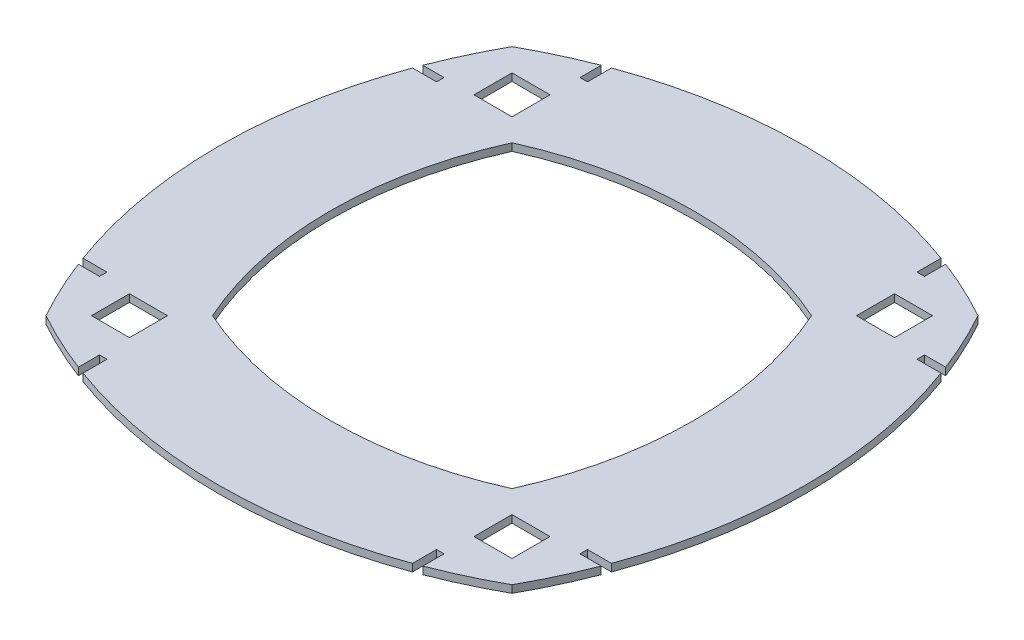
SolidWorks part; units mm, degrees
ref_plane "Front Plane" through (0, 0, 0) normal (0, 0, 1) x (1, 0, 0)
ref_plane "Top Plane" through (0, 0, 0) normal (0, 1, 0) x (1, 0, 0)
ref_plane "Right Plane" through (0, 0, 0) normal (1, 0, 0) x (0, 0, -1)
sketch "Sketch1" plane through (0, 0, 0) normal (0, 1, 0) x (1, 0, 0)
  line L0 (115, 140.4) -> (115, 115)
  line L1 (-155.565, 155.565) -> (155.565, 155.565) construction
  line L2 (-155.565, 155.565) -> (-155.565, -155.565) construction
  line L3 (-155.565, -155.565) -> (155.565, -155.565) construction
  line L4 (155.565, 155.565) -> (155.565, -155.565) construction
  line L5 (0, -155.565) -> (0, 155.565) construction
  line L6 (-155.565, 0) -> (155.565, 0) construction
  line L7 (-140.4, 140.4) -> (140.4, 140.4) construction
  line L8 (-140.4, 140.4) -> (-140.4, -140.4) construction
  line L9 (-140.4, -140.4) -> (140.4, -140.4) construction
  line L10 (140.4, 140.4) -> (140.4, -140.4) construction
  line L11 (0, -140.4) -> (0, 140.4) construction
  line L12 (-140.4, 0) -> (140.4, 0) construction
  line L13 (-140.4, 140.4) -> (-115, 140.4)
  line L14 (-140.4, 140.4) -> (-140.4, 115)
  line L15 (-140.4, 115) -> (-115, 115)
  line L16 (-115, 140.4) -> (-115, 115)
  line L17 (140.4, 140.4) -> (115, 140.4)
  line L18 (140.4, 140.4) -> (140.4, 115)
  line L19 (140.4, 115) -> (115, 115)
  line L20 (140.4, -140.4) -> (140.4, -115)
  line L21 (140.4, -140.4) -> (115, -140.4)
  line L22 (115, -140.4) -> (115, -115)
  line L23 (140.4, -115) -> (115, -115)
  line L24 (-115, -140.4) -> (-115, -115)
  line L25 (-140.4, -140.4) -> (-115, -140.4)
  line L26 (-140.4, -140.4) -> (-140.4, -115)
  line L27 (-140.4, -115) -> (-115, -115)
  line L28 (115, 160.4) -> (110, 160.4)
  line L29 (-115, 160.4) -> (-110, 160.4)
  line L30 (-115, 160.4) -> (-115, 174.545)
  line L31 (110, 160.4) -> (110, 176.4228)
  line L32 (-110, 160.4) -> (-110, 176.4228)
  line L33 (-160.4, 115) -> (-174.545, 115)
  line L34 (-160.4, 115) -> (-160.4, 110)
  line L35 (-160.4, 110) -> (-176.4228, 110)
  line L36 (115, 160.4) -> (115, 174.545)
  line L37 (160.4, 110) -> (176.4228, 110)
  line L38 (160.4, 115) -> (160.4, 110)
  line L39 (160.4, 115) -> (174.545, 115)
  line L40 (160.4, -110) -> (176.4228, -110)
  line L41 (160.4, -115) -> (160.4, -110)
  line L42 (160.4, -115) -> (174.545, -115)
  line L43 (115, -160.4) -> (115, -174.545)
  line L44 (115, -160.4) -> (110, -160.4)
  line L45 (110, -160.4) -> (110, -176.4228)
  line L46 (-110, -160.4) -> (-110, -176.4228)
  line L47 (-115, -160.4) -> (-110, -160.4)
  line L48 (-115, -160.4) -> (-115, -174.545)
  line L49 (-160.4, -115) -> (-160.4, -110)
  line L50 (-160.4, -115) -> (-174.545, -115)
  line L51 (-160.4, -110) -> (-176.4228, -110)
  line L53 (-100, 100) -> (100, 100) construction
  line L54 (-100, 100) -> (-100, -100) construction
  line L55 (-100, -100) -> (100, -100) construction
  line L56 (100, 100) -> (100, -100) construction
  line L57 (0, -100) -> (0, 100) construction
  line L58 (-100, 0) -> (100, 0) construction
  arc A0 (-155.565, 155.565) -> (-115, 174.545) centre (0, -124.0768) cw
  arc A1 (-155.565, -155.565) -> (-174.545, -115) centre (124.0768, 0) cw
  arc A2 (155.565, 155.565) -> (174.545, 115) centre (-124.0768, 0) cw
  arc A3 (-155.565, -155.565) -> (-115, -174.545) centre (0, 124.0768) ccw
  arc A4 (-110, 176.4228) -> (110, 176.4228) centre (0, -124.0768) cw
  arc A5 (-174.545, 115) -> (-155.565, 155.565) centre (124.0768, 0) cw
  arc A6 (115, 174.545) -> (155.565, 155.565) centre (0, -124.0768) cw
  arc A7 (176.4228, 110) -> (176.4228, -110) centre (-124.0768, 0) cw
  arc A8 (174.545, -115) -> (155.565, -155.565) centre (-124.0768, 0) cw
  arc A9 (115, -174.545) -> (155.565, -155.565) centre (0, 124.0768) ccw
  arc A10 (-110, -176.4228) -> (110, -176.4228) centre (0, 124.0768) ccw
  arc A11 (-176.4228, -110) -> (-176.4228, 110) centre (124.0768, 0) cw
  arc A12 (-100, 100) -> (100, 100) centre (0, -124.0768) cw
  arc A13 (100, 100) -> (100, -100) centre (-124.0768, 0) cw
  arc A14 (100, -100) -> (-100, -100) centre (0, 124.0768) cw
  arc A15 (-100, -100) -> (-100, 100) centre (124.0768, 0) cw
  point P0 (0, 0)
  point P8 (0, 0)
  point P56 (0, 0)
  dimension "D2" = 320
  dimension "D1" = 311.13
  dimension "D3" = 280.8
  dimension "D4" = 25.4
  dimension "D5" = 5
  dimension "D6" = 5
  dimension "D7" = 20
  dimension "D8" = 20
  dimension "D9" = 200
extrude "Boss-Extrude1" add sketch "Sketch1" along normal blind 5
